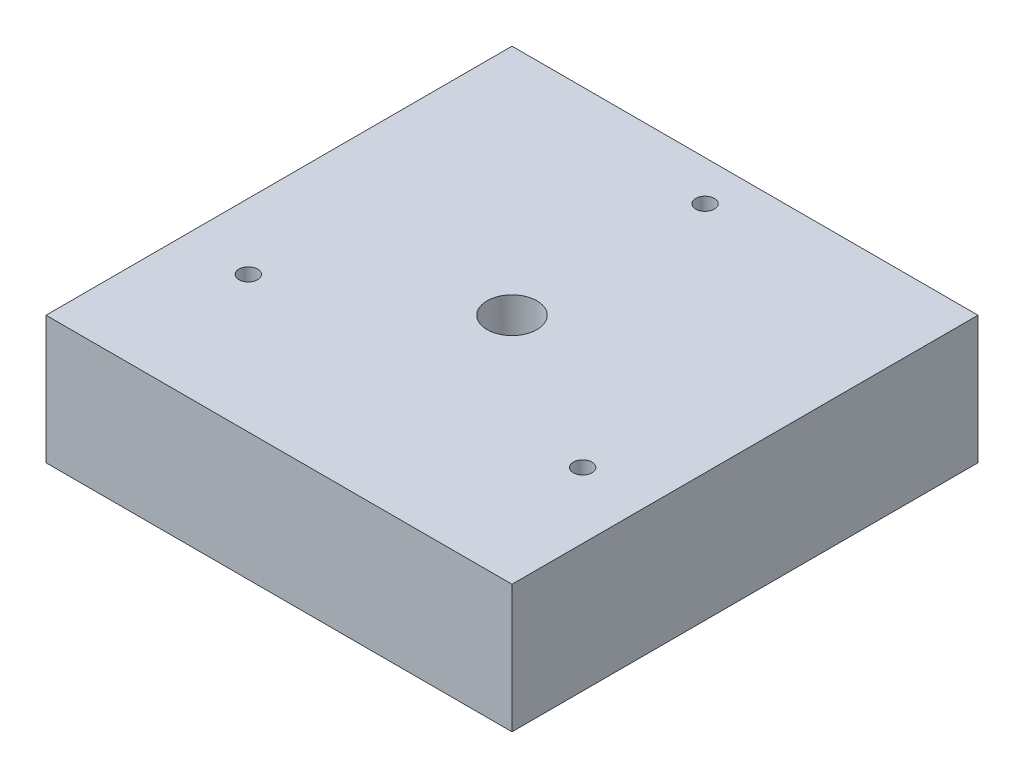
SolidWorks part; units mm, degrees
material "6061 Alloy"
ref_plane "Front Plane" through (0, 0, 0) normal (0, 0, 1) x (1, 0, 0)
ref_plane "Top Plane" through (0, 0, 0) normal (0, 1, 0) x (1, 0, 0)
ref_plane "Right Plane" through (0, 0, 0) normal (1, 0, 0) x (0, 0, -1)
sketch "Sketch1" plane through (0, 0, 0) normal (0, 1, 0) x (1, 0, 0)
  line L0 (0, 0) -> (0, 18.415) construction
  line L1 (0, 0) -> (15.9479, -9.2075) construction
  line L2 (0, 0) -> (-15.9479, -9.2075) construction
  line L4 (-22.225, -22.225) -> (22.225, -22.225)
  line L5 (-22.225, -22.225) -> (-22.225, 22.225)
  line L6 (-22.225, 22.225) -> (22.225, 22.225)
  line L7 (22.225, -22.225) -> (22.225, 22.225)
  line L8 (-22.225, -22.225) -> (22.225, 22.225) construction
  line L9 (-22.225, 22.225) -> (22.225, -22.225) construction
  circle A4 centre (0, 0) radius 2.3812
  circle A5 centre (0, 0) radius 18.415 construction
extrude "Boss-Extrude1" add sketch "Sketch1" along normal blind 3.937
sketch "Sketch3" plane through (0, 0, 0) normal (0, -1, 0) x (1, 0, 0)
  line L1 (-22.225, -22.225) -> (22.225, -22.225)
  line L2 (-22.225, -22.225) -> (-22.225, 22.225)
  line L3 (-22.225, 22.225) -> (22.225, 22.225)
  line L4 (22.225, -22.225) -> (22.225, 22.225)
  line L5 (-22.225, -22.225) -> (22.225, 22.225) construction
  line L6 (-22.225, 22.225) -> (22.225, -22.225) construction
  circle A0 centre (0, 0) radius 2.3812
  point P0 (0, 0)
extrude "Boss-Extrude2" add sketch "Sketch3" along normal blind 8.255
hole_wizard "#2-56 Tapped Hole1" positions "Sketch14" profile "Sketch15" tap size "#2-56" standard "ANSI Inch"
sketch "Sketch14" plane through (0, 3.937, 0) normal (0, 1, 0) x (1, 0, 0)
  point P0 (15.9479, -9.2075)
  point P2 (-15.9479, -9.2075)
  point P4 (0, 18.415)
cosmetic thread "Hole Thread1" parameters "D1"=5.08, "D2"=2.1844
cosmetic thread "Hole Thread2" parameters "D1"=5.08, "D2"=2.1844
cosmetic thread "Hole Thread3" parameters "D1"=5.08, "D2"=2.1844
sketch "Sketch15" plane through (15.9479, 3.937, 9.2075) normal (1, 0, 0) x (0, 0, 1)
  line L0 (0, 0) -> (0, 6.8842)
  line L1 (0, 6.8842) -> (0.889, 6.35)
  line L2 (0.889, 6.35) -> (0.889, 0)
  line L5 (0.889, 0) -> (0, 0)
  line L10 (0, 6.8842) -> (-0.889, 6.35) construction
  line L11 (0, -6.35) -> (0, 107.95) construction
  dimension "Tap Drill Dia." = 1.778
  dimension "Tap Drill Depth" = 6.35
  dimension "Drill Angle" = 118
